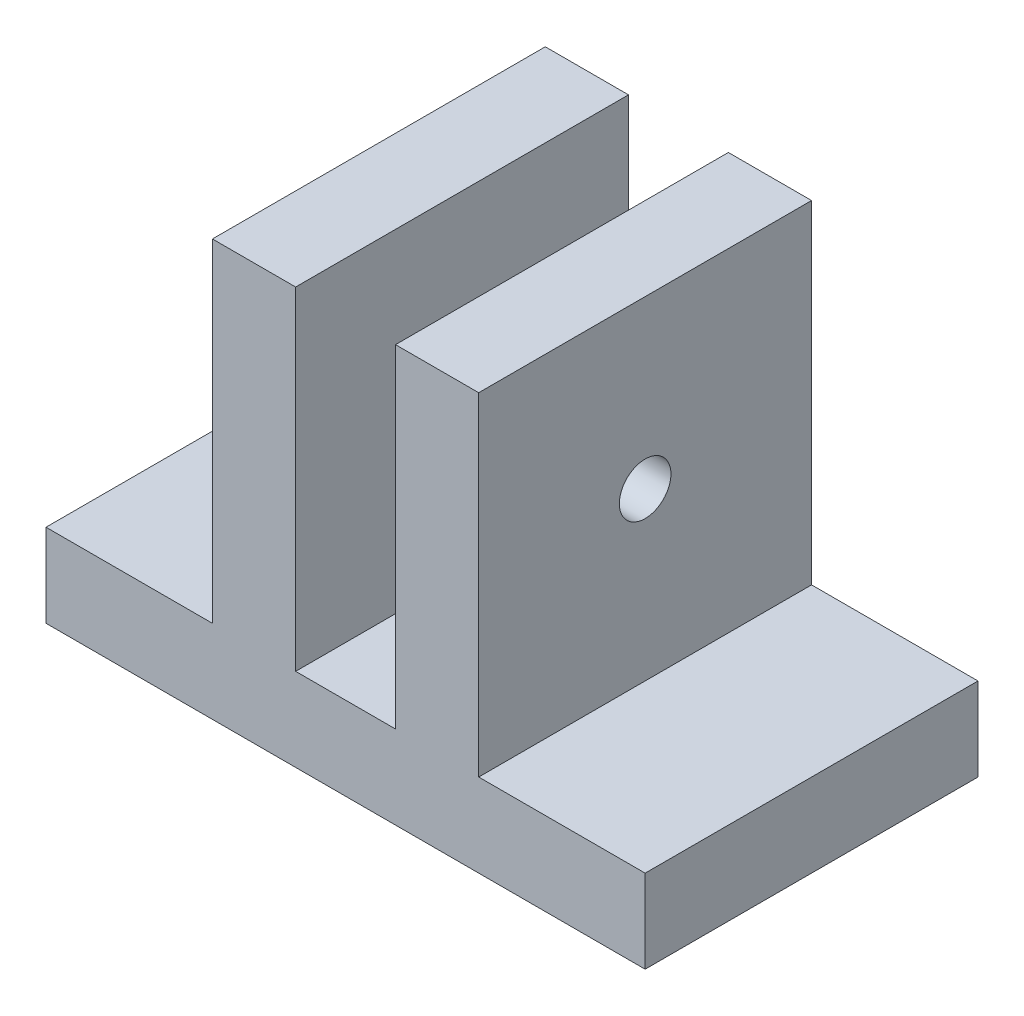
SolidWorks part; units mm, degrees
ref_plane "Front Plane" through (0, 0, 0) normal (0, 0, 1) x (1, 0, 0)
ref_plane "Top Plane" through (0, 0, 0) normal (0, 1, 0) x (1, 0, 0)
ref_plane "Right Plane" through (0, 0, 0) normal (1, 0, 0) x (0, 0, -1)
sketch "Sketch1" plane through (0, 0, 0) normal (0, 0, 1) x (1, 0, 0)
  line L0 (-3, 20) -> (-3, 0)
  line L1 (-3, 0) -> (3, 0)
  line L2 (3, 0) -> (3, 20)
  line L3 (3, 20) -> (8, 20)
  line L4 (8, 20) -> (8, 0)
  line L5 (8, 0) -> (18, 0)
  line L6 (18, 0) -> (18, -5)
  line L7 (18, -5) -> (-18, -5)
  line L8 (-18, -5) -> (-18, 0)
  line L10 (-18, 0) -> (-8, 0)
  line L11 (-8, 0) -> (-8, 20)
  line L12 (-8, 20) -> (-3, 20)
  line L14 (0, 30.7835) -> (0, -30.6461) construction
  line L15 (-48.5681, 0) -> (48.0733, 0) construction
  dimension "D1" = 6
  dimension "D2" = 5
  dimension "D3" = 5
  dimension "D4" = 10
  dimension "D5" = 20
extrude "Boss-Extrude1" add sketch "Sketch1" along normal mid plane 20
sketch "Sketch2" plane through (0, 0, 0) normal (1, 0, 0) x (0, 0, -1)
  line L0 (0, 13.75) -> (0, -13.75) construction
  line L1 (-10, 20) -> (10, 20) construction
  circle A0 centre (0, 10) radius 1.55
  point P4 (0, 10.9268)
  dimension "D1" = 3.1
  dimension "D2" = 10
extrude "Cut-Extrude1" cut sketch "Sketch2" against normal through all both and the other way through all
